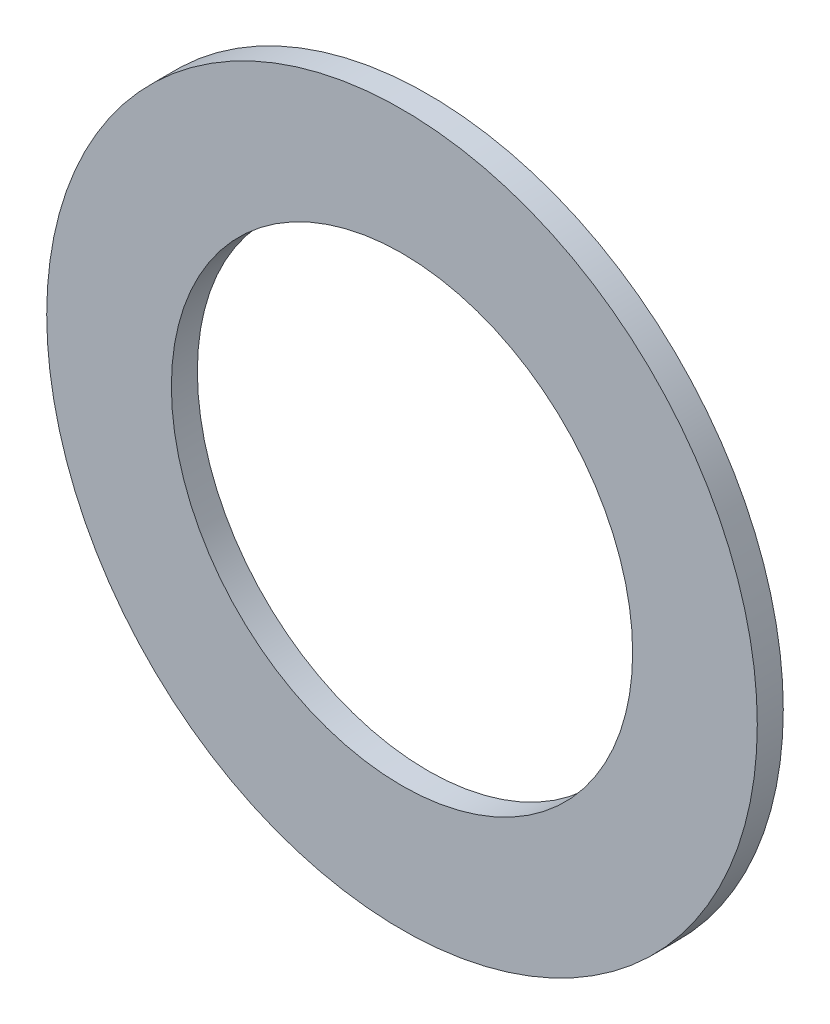
SolidWorks part; units mm, degrees
ref_plane "Front Plane" through (0, 0, 0) normal (0, 0, 1) x (1, 0, 0)
ref_plane "Top Plane" through (0, 0, 0) normal (0, 1, 0) x (1, 0, 0)
ref_plane "Right Plane" through (0, 0, 0) normal (1, 0, 0) x (0, 0, -1)
sketch "Sketch1" plane through (0, 0, 0) normal (0, 0, 1) x (1, 0, 0)
  circle A0 centre (0, 0) radius 5.5562
  circle A1 centre (0, 0) radius 3.6068
  dimension "WasherID" = 7.2136
  dimension "WasherOD" = 11.1125
extrude "Boss-Extrude1" add sketch "Sketch1" along normal blind 0.4064
